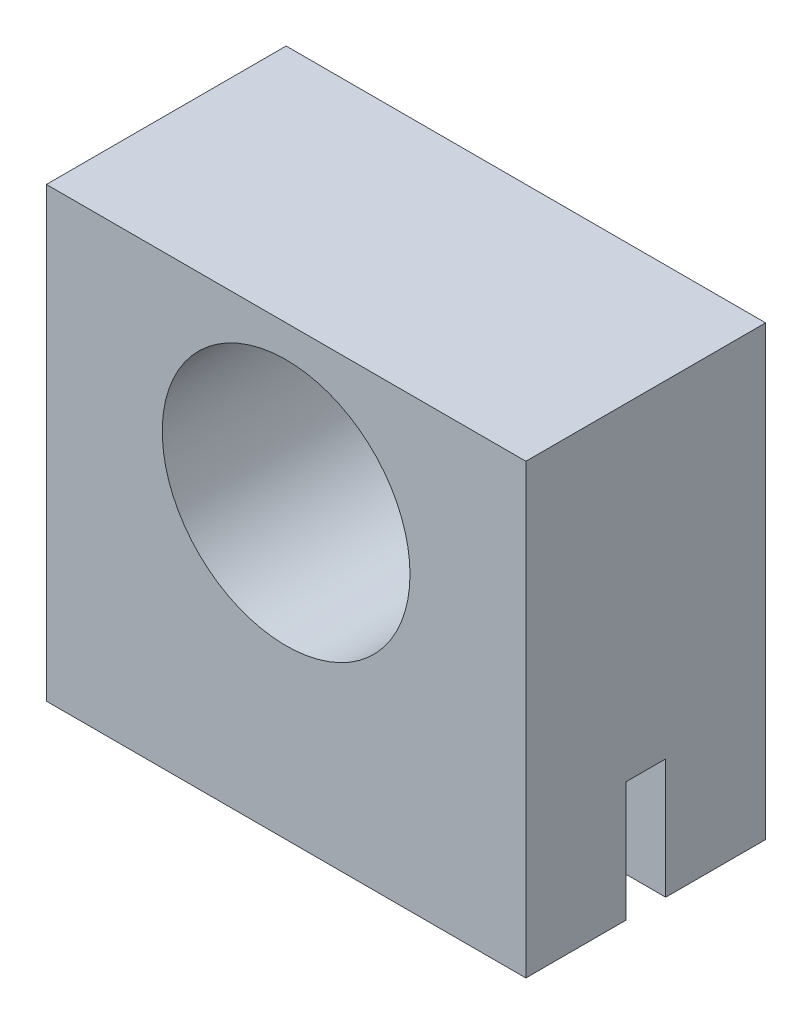
SolidWorks part; units mm, degrees
ref_plane "정면" through (0, 0, 0) normal (0, 0, 1) x (1, 0, 0)
ref_plane "윗면" through (0, 0, 0) normal (0, 1, 0) x (1, 0, 0)
ref_plane "우측면" through (0, 0, 0) normal (1, 0, 0) x (0, 0, -1)
sketch "스케치3" plane through (0, 0, 0) normal (1, 0, 0) x (0, 0, -1)
  line L0 (0, 4.5456) -> (0, -51.4544) construction
  line L1 (-25, -51.4544) -> (25, -51.4544)
  line L2 (-15, 4.5456) -> (15, 4.5456)
  line L3 (-15, 4.5456) -> (-25, -51.4544)
  line L4 (15, 4.5456) -> (25, -51.4544)
  dimension "D2" = 50
  dimension "D3" = 30
  dimension "D4" = 56
extrude "보스-돌출1" add sketch "스케치3" along normal blind 60
sketch "스케치4" plane through (0, 0, 0) normal (0, 0, 1) x (1, 0, 0)
  line L0 (-1.9678, -14.9544) -> (61.9678, -14.9544) construction
  line L1 (30, -51.4544) -> (30, 7.4262) construction
  line L2 (60, -51.4544) -> (0, -51.4544) construction
  circle A0 centre (30, -14.9544) radius 15.5
  dimension "D1" = 31
  dimension "D2" = 21
extrude "컷-돌출1" cut sketch "스케치4" along normal blind 40 and the other way blind 29
sketch "스케치5" plane through (0, 0, 0) normal (1, 0, 0) x (0, 0, -1)
  line L0 (0, 7.2507) -> (0, -19.0866) construction
  line L1 (-25, -51.4544) -> (25, -51.4544) construction
  line L2 (2.5, -66.4544) -> (-2.5, -66.4544)
  line L3 (2.5, -66.4544) -> (2.5, -36.4544)
  line L4 (2.5, -36.4544) -> (-2.5, -36.4544)
  line L5 (-2.5, -66.4544) -> (-2.5, -36.4544)
  line L6 (2.5, -66.4544) -> (-2.5, -36.4544) construction
  line L7 (2.5, -36.4544) -> (-2.5, -66.4544) construction
  point P3 (0, -51.4544)
  dimension "D1" = 5
  dimension "D2" = 30
extrude "컷-돌출2" cut sketch "스케치5" along normal through all
sketch "스케치6" plane through (0, 0, 0) normal (0, 0, 1) x (1, 0, 0)
  line L1 (0, 4.5456) -> (60, 4.5456)
  line L2 (0, 4.5456) -> (0, -51.4544)
  line L3 (0, -51.4544) -> (60, -51.4544)
  line L4 (60, 4.5456) -> (60, -51.4544)
extrude "컷-돌출3" cut sketch "스케치6" against normal blind 10 from offset 25
sketch "스케치7" plane through (0, 0, 0) normal (0, 0, 1) x (1, 0, 0)
  line L1 (0, 4.5456) -> (60, 4.5456)
  line L2 (0, 4.5456) -> (0, -51.4544)
  line L3 (0, -51.4544) -> (60, -51.4544)
  line L4 (60, 4.5456) -> (60, -51.4544)
extrude "컷-돌출4" cut sketch "스케치7" against normal blind 10 from offset 15
